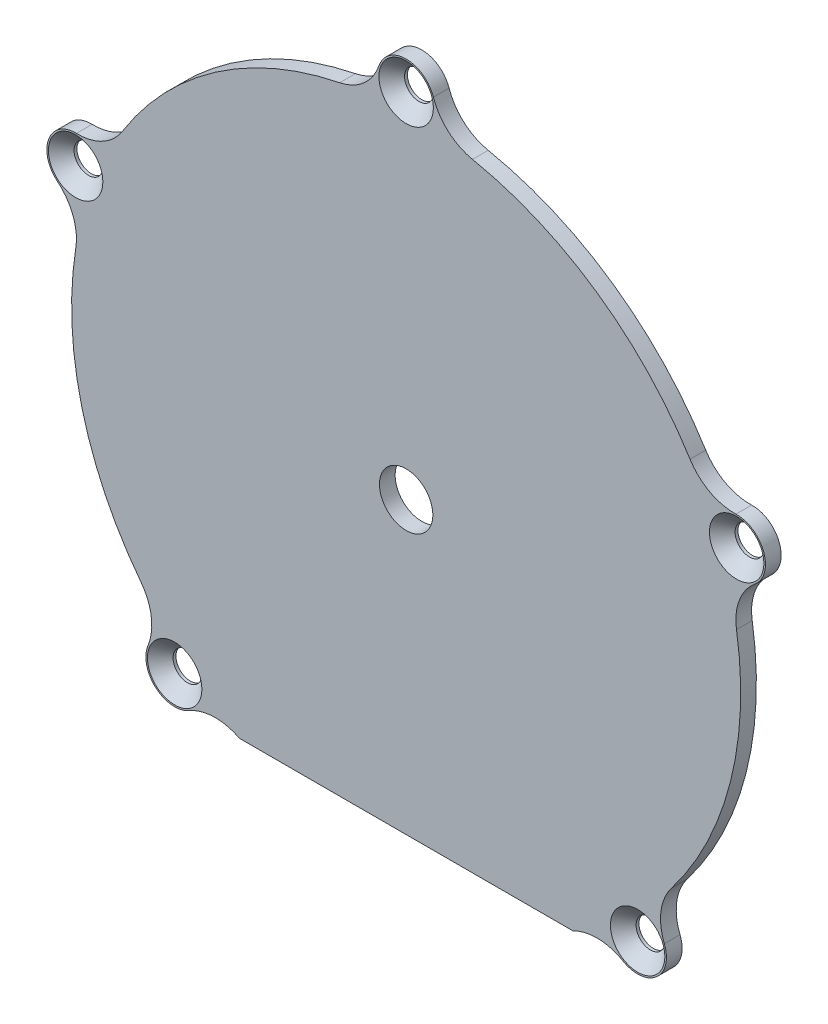
SolidWorks part; units mm, degrees
material "Acrylic (Medium-high impact)"
ref_plane "Front Plane" through (0, 0, 0) normal (0, 0, 1) x (1, 0, 0)
ref_plane "Top Plane" through (0, 0, 0) normal (0, 1, 0) x (1, 0, 0)
ref_plane "Right Plane" through (0, 0, 0) normal (1, 0, 0) x (0, 0, -1)
sketch "Sketch1" plane through (0, 0, 0) normal (0, 0, 1) x (1, 0, 0)
  line L2 (-31.8457, -55.4059) -> (0, -55.4059)
  line L3 (0, -55.4059) -> (31.8457, -55.4059)
  line L4 (-31.8457, -55.4059) -> (0, -55.4059)
  line L5 (0, -55.4059) -> (31.8457, -55.4059)
  arc A21 (-62.9876, 29.104) -> (-66.6313, 19.3585) centre (-63.1372, 23.606) ccw
  arc A22 (-63.1089, 10.0614) -> (-66.6313, 19.3585) centre (-72.9842, 11.6358) ccw
  arc A23 (-63.1089, 10.0614) -> (-50.6603, -38.9551) centre (0, 0) ccw
  arc A24 (-49.3197, -48.8063) -> (-50.6603, -38.9551) centre (-58.5877, -45.0508) ccw
  arc A25 (-49.3197, -48.8063) -> (-41.4645, -55.6305) centre (-44.2223, -50.8719) ccw
  arc A26 (-31.8457, -55.4059) -> (-41.4645, -55.6305) centre (-36.4504, -64.2827) ccw
  arc A29 (41.4645, -55.6305) -> (31.8457, -55.4059) centre (36.4504, -64.2827) ccw
  arc A30 (41.4645, -55.6305) -> (49.3197, -48.8063) centre (44.2223, -50.8719) ccw
  arc A31 (50.6603, -38.9551) -> (49.3197, -48.8063) centre (58.5877, -45.0508) ccw
  arc A32 (50.6603, -38.9551) -> (63.1089, 10.0614) centre (0, 0) ccw
  arc A33 (66.6313, 19.3585) -> (63.1089, 10.0614) centre (72.9842, 11.6358) ccw
  arc A34 (66.6313, 19.3585) -> (62.9876, 29.104) centre (63.1372, 23.606) ccw
  arc A35 (54.2298, 33.8098) -> (62.9876, 29.104) centre (62.7156, 39.1003) ccw
  arc A36 (54.2298, 33.8098) -> (12.677, 62.6359) centre (0, 0) ccw
  arc A37 (5.2022, 69.1912) -> (12.677, 62.6359) centre (14.6607, 72.4372) ccw
  arc A38 (5.2022, 69.1912) -> (-5.2022, 69.1912) centre (0, 67.4059) ccw
  arc A39 (-12.677, 62.6359) -> (-5.2022, 69.1912) centre (-14.6607, 72.4372) ccw
  arc A40 (-12.677, 62.6359) -> (-54.2298, 33.8098) centre (0, 0) ccw
  arc A41 (-62.9876, 29.104) -> (-54.2298, 33.8098) centre (-62.7156, 39.1003) ccw
  arc A42 (-62.9876, 29.104) -> (-66.6313, 19.3585) centre (-63.1372, 23.606) ccw
  arc A43 (-63.1089, 10.0614) -> (-66.6313, 19.3585) centre (-72.9842, 11.6358) ccw
  arc A44 (-63.1089, 10.0614) -> (-50.6603, -38.9551) centre (0, 0) ccw
  arc A45 (-49.3197, -48.8063) -> (-50.6603, -38.9551) centre (-58.5877, -45.0508) ccw
  arc A46 (-49.3197, -48.8063) -> (-41.4645, -55.6305) centre (-44.2223, -50.8719) ccw
  arc A47 (-31.8457, -55.4059) -> (-41.4645, -55.6305) centre (-36.4504, -64.2827) ccw
  arc A50 (41.4645, -55.6305) -> (31.8457, -55.4059) centre (36.4504, -64.2827) ccw
  arc A51 (41.4645, -55.6305) -> (49.3197, -48.8063) centre (44.2223, -50.8719) ccw
  arc A52 (50.6603, -38.9551) -> (49.3197, -48.8063) centre (58.5877, -45.0508) ccw
  arc A53 (50.6603, -38.9551) -> (63.1089, 10.0614) centre (0, 0) ccw
  arc A54 (66.6313, 19.3585) -> (63.1089, 10.0614) centre (72.9842, 11.6358) ccw
  arc A55 (66.6313, 19.3585) -> (62.9876, 29.104) centre (63.1372, 23.606) ccw
  arc A56 (54.2298, 33.8098) -> (62.9876, 29.104) centre (62.7156, 39.1003) ccw
  arc A57 (54.2298, 33.8098) -> (12.677, 62.6359) centre (0, 0) ccw
  arc A58 (5.2022, 69.1912) -> (12.677, 62.6359) centre (14.6607, 72.4372) ccw
  arc A59 (5.2022, 69.1912) -> (-5.2022, 69.1912) centre (0, 67.4059) ccw
  arc A60 (-12.677, 62.6359) -> (-5.2022, 69.1912) centre (-14.6607, 72.4372) ccw
  arc A61 (-12.677, 62.6359) -> (-54.2298, 33.8098) centre (0, 0) ccw
  arc A62 (-62.9876, 29.104) -> (-54.2298, 33.8098) centre (-62.7156, 39.1003) ccw
  dimension "D1" = 0
extrude "Boss-Extrude1" add sketch "Sketch1" along normal blind 3
hole_wizard "CSK for M5 Countersunk Flat Head Screw1" positions "Sketch2" profile "Sketch3" countersink size "M5" standard "ISO" end condition through all
sketch "Sketch2" plane through (0, 0, 3) normal (0, 0, 1) x (1, 0, 0)
  point P0 (-63.1372, 23.606)
  point P3 (0, 67.4059)
  point P6 (63.1372, 23.606)
  point P9 (44.2223, -50.8719)
  point P12 (-44.2223, -50.8719)
sketch "Sketch3" plane through (-63.1372, 23.606, 3) normal (1, 0, 0) x (0, -1, 0)
  line L0 (0, 0) -> (0, 3)
  line L1 (0, 3) -> (2.75, 3)
  line L2 (2.75, 3) -> (2.75, 2.45)
  line L3 (2.75, 2.45) -> (5.2, 0)
  line L5 (5.2, 0) -> (0, 0)
  line L6 (-2.75, 2.45) -> (-5.2, 0) construction
  line L11 (0, -6.35) -> (0, 107.95) construction
  dimension "Thru Hole Dia." = 5.5
  dimension "Thru Hole Depth" = 3
  dimension "Near C'Sink Dia." = 10.4
  dimension "Near C'Sink Angle" = 90
sketch "Sketch7" plane through (0, 0, 3) normal (0, 0, 1) x (1, 0, 0)
  circle A0 centre (0, 0) radius 5.1
  dimension "D1" = 10.2
extrude "Cut-Extrude1" cut sketch "Sketch7" against normal through all
